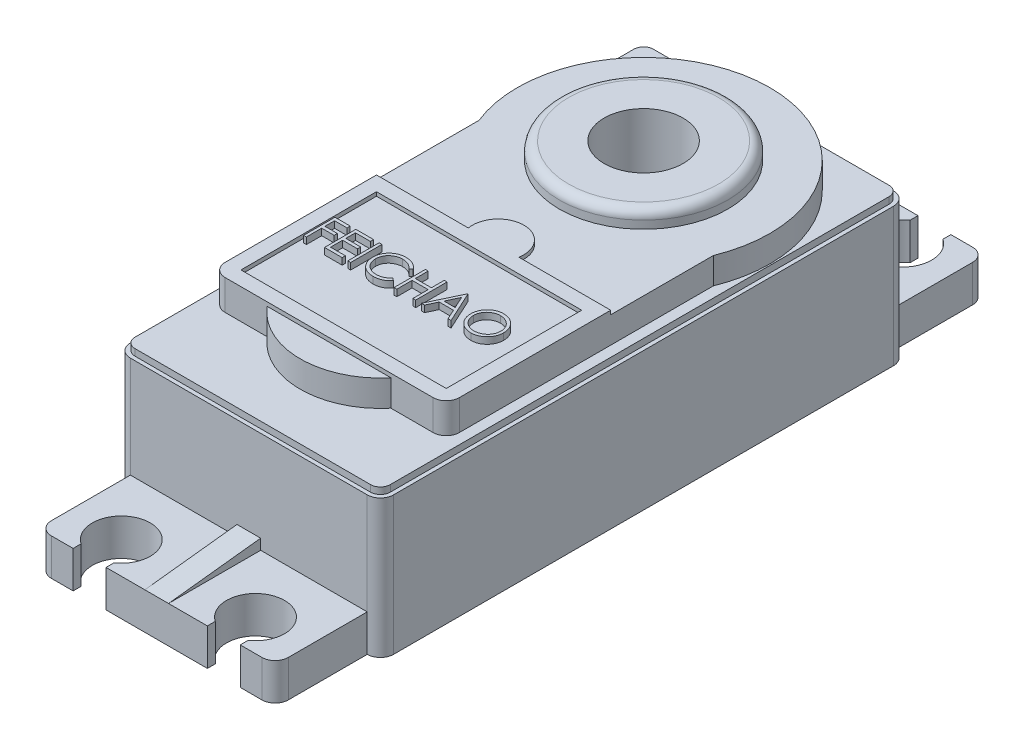
SolidWorks part; units mm, degrees
material "PC High Viscosity"
ref_plane "Front Plane" through (0, 0, 0) normal (0, 0, 1) x (1, 0, 0)
ref_plane "Top Plane" through (0, 0, 0) normal (0, 1, 0) x (1, 0, 0)
ref_plane "Right Plane" through (0, 0, 0) normal (1, 0, 0) x (0, 0, -1)
sketch "BaseS" plane through (0, 0, 0) normal (0, 1, 0) x (1, 0, 0)
  line L1 (-10, 20) -> (10, 20)
  line L2 (-10, 20) -> (-10, -20)
  line L3 (-10, -20) -> (10, -20)
  line L4 (10, 20) -> (10, -20)
  line L5 (-10, 20) -> (10, -20) construction
  line L6 (-10, -20) -> (10, 20) construction
  point P0 (0, 0)
  dimension "D1" = 20
  dimension "D2" = 40
extrude "BASE" add sketch "BaseS" along normal blind 11 contours L4 L3 L2 L1
sketch "ShaftHoleS" plane through (0, 11, 0) normal (0, 1, 0) x (1, 0, 0)
  line L0 (0, 10) -> (0, 20) construction
  line L1 (-10, 20) -> (10, 20) construction
  circle A0 centre (0, 10) radius 3
  dimension "D1" = 6
  dimension "D2" = 10
extrude "SHAFT HOLE" cut sketch "ShaftHoleS" against normal through all
sketch "MountingTabS" plane through (0, 0, 20) normal (0, 0, 1) x (1, 0, 0)
  line L0 (-10, 0) -> (10, 0) construction
  line L1 (-9, 2.8) -> (9, 2.8)
  line L2 (-9, 2.8) -> (-9, 0)
  line L3 (-9, 0) -> (9, 0)
  line L4 (9, 2.8) -> (9, 0)
  line L5 (-9, 2.8) -> (9, 0) construction
  line L6 (-9, 0) -> (9, 2.8) construction
  line L7 (10, 11) -> (10, 0) construction
  point P0 (0, 1.4)
  dimension "D1" = 1
  dimension "D2" = 2.8
  dimension "D3" = 18
extrude "MOUNTING TAB" add sketch "MountingTabS" along normal blind 7
sketch "MountingHoleS" plane through (0, 2.8, 0) normal (0, 1, 0) x (1, 0, 0)
  line L0 (0, -27) -> (0, -20) construction
  line L1 (-6.35, -26.4) -> (-6.35, -27)
  line L2 (-6.35, -27) -> (-3.85, -27)
  line L3 (-3.85, -27) -> (-3.85, -26.4)
  line L4 (-5.1, -24.5896) -> (-5.1, -27) construction
  line L5 (9, -20) -> (-9, -20) construction
  line L6 (9, -27) -> (-9, -27) construction
  line L7 (-9, -27) -> (-9, -20) construction
  arc A0 (-3.85, -26.4) -> (-6.35, -26.4) centre (-5.1, -24.5896) ccw
  dimension "D1" = 4.4
  dimension "D2" = 3.9
  dimension "D3" = 2.5
  dimension "D4" = 0.6
extrude "MOUNTING HOLE" cut sketch "MountingHoleS" against normal through all
mirror "MH M" about plane through (0, 0, 0) normal (1, 0, 0) of "MOUNTING HOLE"
sketch "BottomAlignHoleS" plane through (0, 0, 0) normal (0, -1, 0) x (1, 0, 0)
  line L0 (0, 27) -> (0, 25) construction
  line L1 (-3.85, 27) -> (3.85, 27) construction
  circle A0 centre (0, 25) radius 0.7
  dimension "D1" = 1.4
  dimension "D2" = 2
extrude "BOTTOM ALIGN HOLE" cut sketch "BottomAlignHoleS" against normal blind 0.5
sketch "TriangularTabS" plane through (0, 0, 0) normal (1, 0, 0) x (0, 0, -1)
  line L0 (-20, 2.8) -> (-27, 2.8)
  line L1 (-27, 2.8) -> (-20, 3.6)
  line L2 (-20, 3.6) -> (-20, 2.8)
  line L3 (-26.4, 2.8) -> (-27, 2.8) construction
  dimension "D1" = 0.8
extrude "TRIANGULAR TAB" add sketch "TriangularTabS" along normal mid plane 1.8
mirror "MOUNTING TAB FEATURES M" about plane through (0, 0, 0) normal (0, 0, 1) of "TRIANGULAR TAB", "BOTTOM ALIGN HOLE", "MH M", "MOUNTING HOLE", "MOUNTING TAB"
sketch "BaseTopBodyS" plane through (0, 11, 0) normal (0, 1, 0) x (1, 0, 0)
  line L0 (-8.9, -13.8986) -> (8.9, -13.8986)
  line L1 (8.9, -13.8986) -> (8.9, 6.4014)
  line L2 (-8.9, -13.8986) -> (-8.9, 6.4014)
  line L3 (0, -13.8986) -> (0, 0) construction
  arc A0 (8.9, 6.4014) -> (-8.9, 6.4014) centre (0, 10) ccw
  circle A1 centre (0, 10) radius 3
  circle A2 centre (0, 10) radius 3 construction
  dimension "D1" = 19.2
  dimension "D2" = 17.8
  dimension "D3" = 20.3
extrude "BASE TOP BODY" add sketch "BaseTopBodyS" along normal blind 2
sketch "PartCircleS" plane through (0, 11, 0) normal (0, 1, 0) x (1, 0, 0)
  line L0 (-4.7, -13.8986) -> (4.7, -13.8986) construction
  line L1 (0, -13.8986) -> (0, -16.0986) construction
  line L2 (-4.7, -13.8986) -> (4.7, -13.8986)
  line L3 (-8.9, -13.8986) -> (8.9, -13.8986) construction
  arc A0 (-4.7, -13.8986) -> (4.7, -13.8986) centre (0, -9.9782) ccw
  dimension "D1" = 2.2
  dimension "D2" = 9.4
extrude "PART CIRCLE" add sketch "PartCircleS" along normal up to surface (2 mm away) up to face at (0, 13, 0.449)
sketch "TopBodyCylinder1" plane through (0, 13, 0) normal (0, 1, 0) x (1, 0, 0)
  circle A0 centre (0, 10) radius 3
  circle A1 centre (0, 10) radius 6.4
  circle A2 centre (0, 10) radius 3 construction
  dimension "D1" = 12.8
extrude "TOP BODY CYLINDER 1" add sketch "TopBodyCylinder1" along normal blind 1.3
sketch "TopBodyLabelNest" plane through (0, 13, 0) normal (0, 1, 0) x (1, 0, 0)
  line L0 (-8.9, -1.3986) -> (8.9, -1.3986)
  line L1 (-8.9, -1.3986) -> (-8.9, -13.8986)
  line L2 (-8.9, -13.8986) -> (8.9, -13.8986)
  line L3 (8.9, -1.3986) -> (8.9, -13.8986)
  line L4 (-8.9, -1.3986) -> (8.9, -13.8986) construction
  line L5 (-8.9, -13.8986) -> (8.9, -1.3986) construction
  line L6 (-7.8, -2.4986) -> (7.8, -2.4986)
  line L7 (-7.8, -2.4986) -> (-7.8, -12.7986)
  line L8 (-7.8, -12.7986) -> (7.8, -12.7986)
  line L9 (7.8, -2.4986) -> (7.8, -12.7986)
  line L10 (-7.8, -2.4986) -> (7.8, -12.7986) construction
  line L11 (-7.8, -12.7986) -> (7.8, -2.4986) construction
  line L12 (8.9, -13.8986) -> (8.9, 6.4014) construction
  line L13 (0, -2.4986) -> (0, -1.3986) construction
  line L14 (-7.8, -7.6486) -> (-8.9, -7.6486) construction
  point P0 (0, -7.6486)
  point P5 (0, -7.6486)
  dimension "D1" = 12.5
  dimension "D2" = 1.1
extrude "TOP BODY LABEL NEST" add sketch "TopBodyLabelNest" along normal blind 0.3
sketch "PartCircle2S" plane through (0, 13, 0) normal (0, 1, 0) x (1, 0, 0)
  line L0 (1.3038, -2.4986) -> (-1.3038, -2.4986)
  line L1 (0, -2.4986) -> (0, 3.6) construction
  line L2 (0, 0.9014) -> (0, 3.6) construction
  line L3 (7.8, -2.4986) -> (-7.8, -2.4986) construction
  arc A0 (1.3038, -2.4986) -> (-1.3038, -2.4986) centre (0, -1.0486) ccw
  circle A1 centre (0, 10) radius 6.4 construction
  dimension "D2" = 1.95
  dimension "D1" = 3.4
extrude "PART CIRCLE 2" add sketch "PartCircle2S" along normal up to surface (0.3 mm away) up to face at (0, 13.3, 7.6486)
sketch "BorderCutS" plane through (0, 11, 0) normal (0, 1, 0) x (1, 0, 0)
  line L0 (-9.7, 19.7) -> (-9.7, -19.7)
  line L1 (-9.7, -19.7) -> (9.7, -19.7)
  line L2 (9.7, -19.7) -> (9.7, 19.7)
  line L3 (9.7, 19.7) -> (-9.7, 19.7)
  line L4 (-10, 20) -> (-10, -20)
  line L5 (-10, -20) -> (10, -20)
  line L6 (10, -20) -> (10, 20)
  line L7 (10, 20) -> (-10, 20)
  line L8 (-10, 0) -> (-9.7, 0) construction
  line L9 (0, -20) -> (0, -19.7) construction
  dimension "D1" = 0.3
extrude "BORDER CUT" cut sketch "BorderCutS" against normal blind 0.5
fillet "MAIN BODY FEATURES F" radius 1 10 edges at (9, 1.4, -27) (-9, 1.4, -27) (-10, 5.25, -20) (10, 5.25, -20) (-8.9, 12.15, 13.8986) (8.9, 12.15, 13.8986) (-10, 5.25, 20) (10, 5.25, 20) (9, 1.4, 27) (-9, 1.4, 27)
fillet "BORDER CUT F" radius 0.75 4 edges at (-9.7, 10.75, -19.7) (9.7, 10.75, -19.7) (9.7, 10.75, 19.7) (-9.7, 10.75, 19.7)
sketch "Esquisse1" plane through (0, 13, 0) normal (0, 1, 0) x (1, 0, 0)
  line L0 (-7.8, -2.4986) -> (-7.8, -12.7986) construction
  text T0 "FEICHAO\r\n" font "Century Gothic" height in points 9
extrude "Boss.-Extru.1" add sketch "Esquisse1" along normal blind 0.5
fillet "Congé1" radius 0.7 1 edges at (0, 14.3, -3.6)
